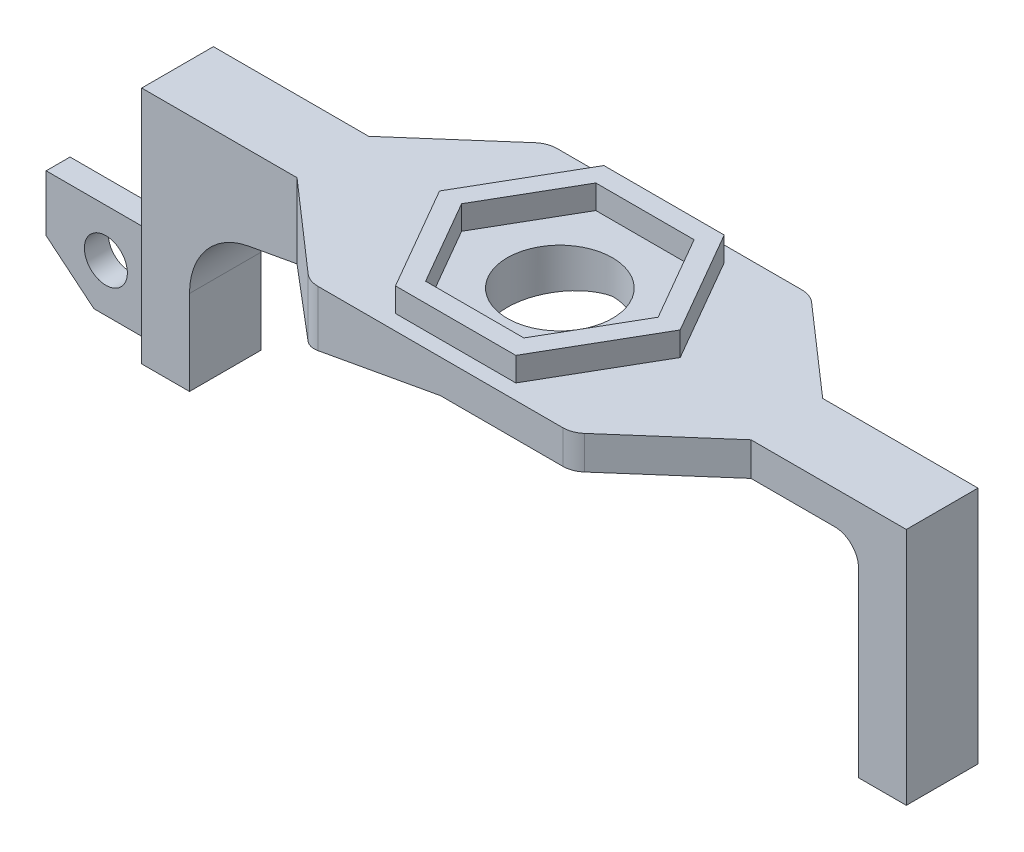
SolidWorks part; units mm, degrees
ref_plane "Front Plane" through (0, 0, 0) normal (0, 0, 1) x (1, 0, 0)
ref_plane "Top Plane" through (0, 0, 0) normal (0, 1, 0) x (1, 0, 0)
ref_plane "Right Plane" through (0, 0, 0) normal (1, 0, 0) x (0, 0, -1)
sketch "Sketch2" plane through (0, 0, 0) normal (0, 0, 1) x (1, 0, 0)
  line L0 (160, 0) -> (-160, 0)
  line L1 (-160, 0) -> (-160, -100)
  line L2 (-160, -100) -> (-140, -100)
  line L3 (140, -100) -> (160, -100)
  line L4 (160, -100) -> (160, 0)
  line L5 (140, -100) -> (140, -14)
  line L6 (140, -14) -> (0, -14)
  line L7 (-140, -100) -> (-140, -39.4274)
  line L8 (-140, -39.4274) -> (0, -14)
extrude "Boss-Extrude1" add sketch "Sketch2" along normal blind 100
fillet "Fillet1" radius 30 1 edges at (-140, -39.4274, 50)
fillet "Fillet2" radius 10 1 edges at (140, -14, 50)
sketch "Sketch5" plane through (0, 0, 0) normal (0, 1, 0) x (1, 0, 0)
  line L0 (-160, 0) -> (-160, -35)
  line L1 (-160, -100) -> (-160, 0) construction
  line L2 (-160, 0) -> (-55, 0)
  line L3 (160, 0) -> (-160, 0) construction
  line L4 (-160, -35) -> (-95, -35)
  line L5 (-95, -35) -> (-55, 0)
extrude "Cut-Extrude1" cut sketch "Sketch5" against normal blind 100
sketch "Sketch6" plane through (0, 0, 0) normal (0, 1, 0) x (1, 0, 0)
  line L0 (-160, -100) -> (-160, -65)
  line L1 (-160, -100) -> (-160, -35) construction
  line L2 (-160, -65) -> (-95, -65)
  line L3 (-160, -100) -> (-55, -100)
  line L4 (160, -100) -> (-160, -100) construction
  line L5 (-95, -65) -> (-55, -100)
extrude "Cut-Extrude2" cut sketch "Sketch6" against normal blind 100
sketch "Sketch7" plane through (0, 0, 0) normal (0, 1, 0) x (1, 0, 0)
  line L0 (160, 0) -> (160, -34.9995)
  line L1 (160, -100) -> (160, 0) construction
  line L2 (160, -34.9995) -> (95, -34.9995)
  line L3 (160, 0) -> (55, 0)
  line L4 (160, 0) -> (-55, 0) construction
  line L5 (55, 0) -> (95, -34.9995)
extrude "Cut-Extrude3" cut sketch "Sketch7" against normal blind 100
sketch "Sketch8" plane through (0, 0, 0) normal (0, 1, 0) x (1, 0, 0)
  line L0 (160, -100) -> (160, -65)
  line L1 (160, -100) -> (160, -34.9995) construction
  line L2 (160, -65) -> (95, -65)
  line L3 (160, -100) -> (55, -100)
  line L4 (160, -100) -> (-55, -100) construction
  line L5 (55, -100) -> (95, -65)
extrude "Cut-Extrude4" cut sketch "Sketch8" against normal blind 100
fillet "Fillet3" radius 10 4 edges at (-55, -11.9947, 100) (55, -7, 100) (55, -7, 0) (-55, -11.9947, 0)
sketch "Sketch9" plane through (0, 0, 0) normal (0, 1, 0) x (1, 0, 0)
  circle A0 centre (0, -50) radius 22
extrude "Cut-Extrude5" cut sketch "Sketch9" against normal blind 100
sketch "Sketch10" plane through (0, 0, 0) normal (0, 1, 0) x (1, 0, 0)
  line L1 (-25.1822, -6.3831) -> (-50.3644, -50)
  line L2 (-50.3644, -50) -> (-25.1822, -93.6169)
  line L3 (-25.1822, -93.6169) -> (25.1822, -93.6169)
  line L4 (25.1822, -93.6169) -> (50.3644, -50)
  line L5 (50.3644, -50) -> (25.1822, -6.3831)
  line L6 (25.1822, -6.3831) -> (-25.1822, -6.3831)
extrude "Boss-Extrude2" add sketch "Sketch10" along normal blind 10
sketch "Sketch11" plane through (0, 10, 0) normal (0, 1, 0) x (1, 0, 0)
  circle A0 centre (0, -50) radius 22
extrude "Cut-Extrude6" cut sketch "Sketch11" against normal blind 10
sketch "Sketch12" plane through (0, 10, 0) normal (0, 1, 0) x (1, 0, 0)
  line L27 (41.1268, -50) -> (20.5634, -14.3831)
  line L28 (20.5634, -85.6169) -> (41.1268, -50)
  line L29 (-20.5634, -85.6169) -> (20.5634, -85.6169)
  line L30 (-41.1268, -50) -> (-20.5634, -85.6169)
  line L31 (-20.5634, -14.3831) -> (-41.1268, -50)
  line L32 (20.5634, -14.3831) -> (-20.5634, -14.3831)
  line L33 (41.1268, -50) -> (20.5634, -14.3831)
  line L34 (20.5634, -85.6169) -> (41.1268, -50)
  line L35 (-20.5634, -85.6169) -> (20.5634, -85.6169)
  line L36 (-41.1268, -50) -> (-20.5634, -85.6169)
  line L37 (-20.5634, -14.3831) -> (-41.1268, -50)
  line L38 (20.5634, -14.3831) -> (-20.5634, -14.3831)
  dimension "D1" = 8
extrude "Cut-Extrude7" cut sketch "Sketch12" against normal blind 10
ref_plane "Plane2" through (0, 0, 50) normal (0, 0, 1) x (1, 0, 0)
sketch "Sketch14" plane through (0, 0, 50) normal (0, 0, 1) x (1, 0, 0)
  line L0 (-160, -100) -> (-160, -60)
  line L1 (-160, -100) -> (-160, 0) construction
  line L2 (-160, -60) -> (-210, -60)
  line L6 (-160, -100) -> (-190, -100)
  line L7 (-190, -100) -> (-210.0563, -83.4548)
  line L8 (-210.0563, -83.4548) -> (-210, -60)
extrude "Boss-Extrude3" add sketch "Sketch14" along normal blind 5 and the other way blind 5
sketch "Sketch15" plane through (0, 0, 55) normal (0, 0, 1) x (1, 0, 0)
  circle A0 centre (-185, -80) radius 9
extrude "Cut-Extrude10" cut sketch "Sketch15" against normal through all and the other way through all
